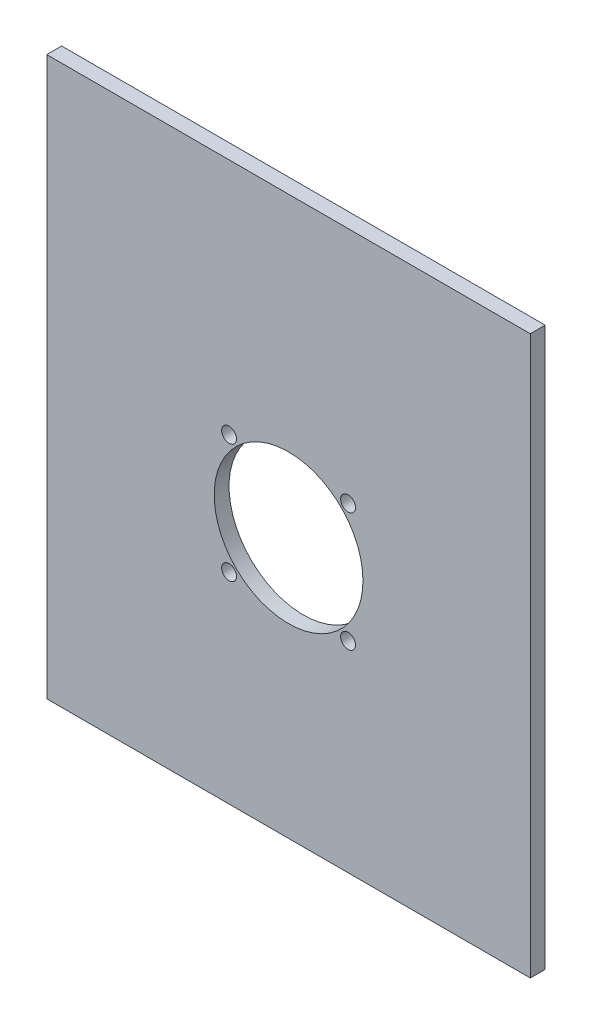
SolidWorks part; units mm, degrees
ref_plane "Front Plane" through (0, 0, 0) normal (0, 0, 1) x (1, 0, 0)
ref_plane "Top Plane" through (0, 0, 0) normal (0, 1, 0) x (1, 0, 0)
ref_plane "Right Plane" through (0, 0, 0) normal (1, 0, 0) x (0, 0, -1)
sketch "Sketch1" plane through (0, 0, 0) normal (0, 0, 1) x (1, 0, 0)
  line L1 (-112.8247, 64.3669) -> (17.1753, 64.3669)
  line L2 (-112.8247, 64.3669) -> (-112.8247, -85.6331)
  line L3 (-112.8247, -85.6331) -> (17.1753, -85.6331)
  line L4 (17.1753, 64.3669) -> (17.1753, -85.6331)
  dimension "D1" = 130
  dimension "D2" = 150
extrude "Boss-Extrude1" add sketch "Sketch1" along normal blind 4
sketch "Sketch3" plane through (0, 0, 4) normal (0, 0, 1) x (1, 0, 0)
  line L0 (-47.8247, -85.6331) -> (-47.8247, -15.6331) construction
  line L1 (-112.8247, -85.6331) -> (17.1753, -85.6331) construction
  line L2 (-63.8247, 0.3669) -> (-31.8247, -31.6331) construction
  line L3 (-63.8247, -31.6331) -> (-31.8247, 0.3669) construction
  circle A0 centre (-63.8247, 0.3669) radius 2
  circle A1 centre (-47.8247, -15.6331) radius 20
  circle A2 centre (-31.8247, 0.3669) radius 2
  circle A3 centre (-31.8247, -31.6331) radius 2
  circle A4 centre (-63.8247, -31.6331) radius 2
  point P25 (-47.8247, -15.6331)
  dimension "D1" = 32
  dimension "D3" = 4
  dimension "D4" = 4
  dimension "D2" = 32
sketch "Sketch9" plane through (0, 0, 4) normal (0, 0, 1) x (1, 0, 0)
  line L0 (-47.8247, -85.6331) -> (-47.8247, -15.6331) construction
  line L1 (-112.8247, -85.6331) -> (17.1753, -85.6331) construction
  circle A0 centre (-47.8247, -15.6331) radius 20
extrude "Cut-Extrude4" cut sketch "Sketch9" against normal blind 4 contours A0
extrude "Cut-Extrude5" cut sketch "Sketch3" against normal blind 4 contours A0 | A4 | A3 | A2
